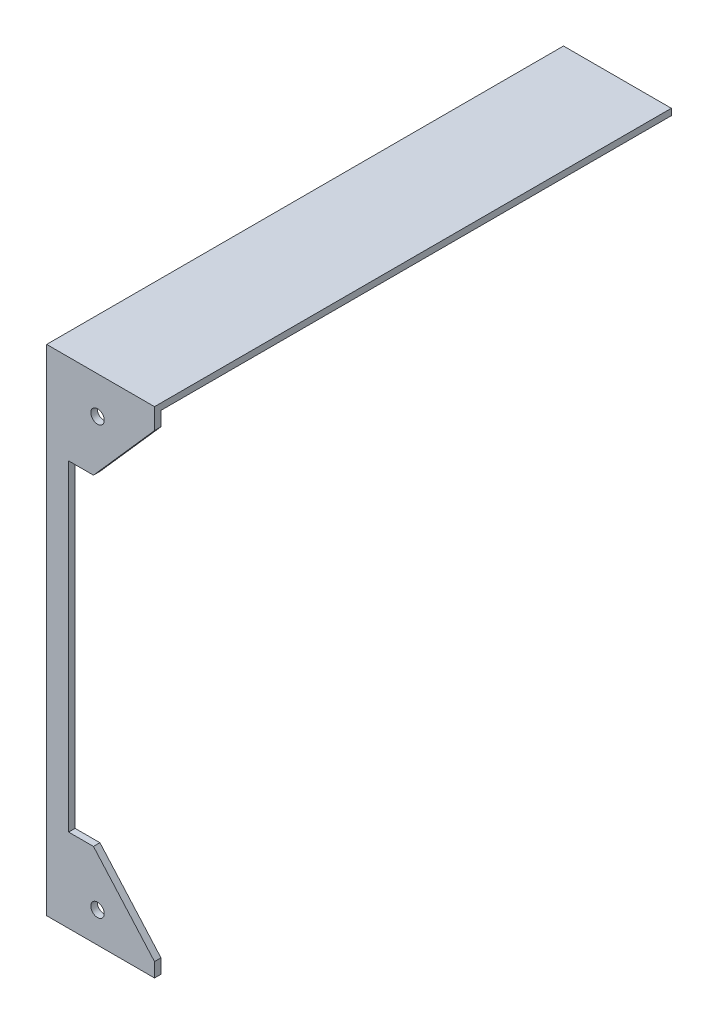
SolidWorks part; units mm, degrees
ref_plane "Front Plane" through (0, 0, 0) normal (0, 0, 1) x (1, 0, 0)
ref_plane "Top Plane" through (0, 0, 0) normal (0, 1, 0) x (1, 0, 0)
ref_plane "Right Plane" through (0, 0, 0) normal (1, 0, 0) x (0, 0, -1)
sketch "Sketch1" plane through (0, 0, 0) normal (0, 0, 1) x (1, 0, 0)
  line L0 (-250, 120) -> (0, 120) construction
  line L1 (-238.5, 99.5) -> (-223.5, 116.5) construction
  line L2 (-244.6, 99.5) -> (-238.5, 99.5) construction
  line L3 (-244.6, 20.5) -> (-244.6, 99.5) construction
  line L4 (-250, 2) -> (-250, 118) construction
  line L5 (0, 0) -> (-250, 0) construction
  line L6 (-238.5, 20.5) -> (-244.6, 20.5) construction
  line L7 (-223.5, 3.5) -> (-238.5, 20.5) construction
  line L8 (-250, 120) -> (-223.5, 120)
  line L9 (-238.5, 99.5) -> (-223.5, 116.5)
  line L10 (-244.6, 99.5) -> (-238.5, 99.5)
  line L11 (-244.6, 20.5) -> (-244.6, 99.5)
  line L12 (-250, 0) -> (-250, 120)
  line L13 (-223.5, 0) -> (-250, 0)
  line L14 (-238.5, 20.5) -> (-244.6, 20.5)
  line L15 (-223.5, 3.5) -> (-238.5, 20.5)
  line L16 (-223.5, 116.5) -> (-223.5, 120)
  line L17 (-223.5, 3.5) -> (-223.5, 0)
  arc A0 (-239.15, 112.5) -> (-235.85, 112.5) centre (-237.5, 112.5) ccw construction
  arc A1 (-235.85, 112.5) -> (-239.15, 112.5) centre (-237.5, 112.5) ccw construction
  arc A2 (-235.85, 7.5) -> (-239.15, 7.5) centre (-237.5, 7.5) ccw construction
  arc A3 (-239.15, 7.5) -> (-235.85, 7.5) centre (-237.5, 7.5) ccw construction
  arc A4 (-239.15, 112.5) -> (-235.85, 112.5) centre (-237.5, 112.5) ccw
  arc A5 (-235.85, 112.5) -> (-239.15, 112.5) centre (-237.5, 112.5) ccw
  arc A6 (-235.85, 7.5) -> (-239.15, 7.5) centre (-237.5, 7.5) ccw
  arc A7 (-239.15, 7.5) -> (-235.85, 7.5) centre (-237.5, 7.5) ccw
extrude "Boss-Extrude1" add sketch "Sketch1" along normal blind 1.5875
sketch "Sketch2" plane through (0, 120, 0) normal (0, 1, 0) x (1, 0, 0)
  line L0 (-223.5, -1.5875) -> (-250, -1.5875)
  line L1 (-250, -1.5875) -> (-250, 125.4125)
  line L2 (-250, 125.4125) -> (-223.5, 125.4125)
  line L3 (-223.5, 125.4125) -> (-223.5, -1.5875)
  dimension "D1" = 127
extrude "Boss-Extrude2" add sketch "Sketch2" along normal blind 1.5875
